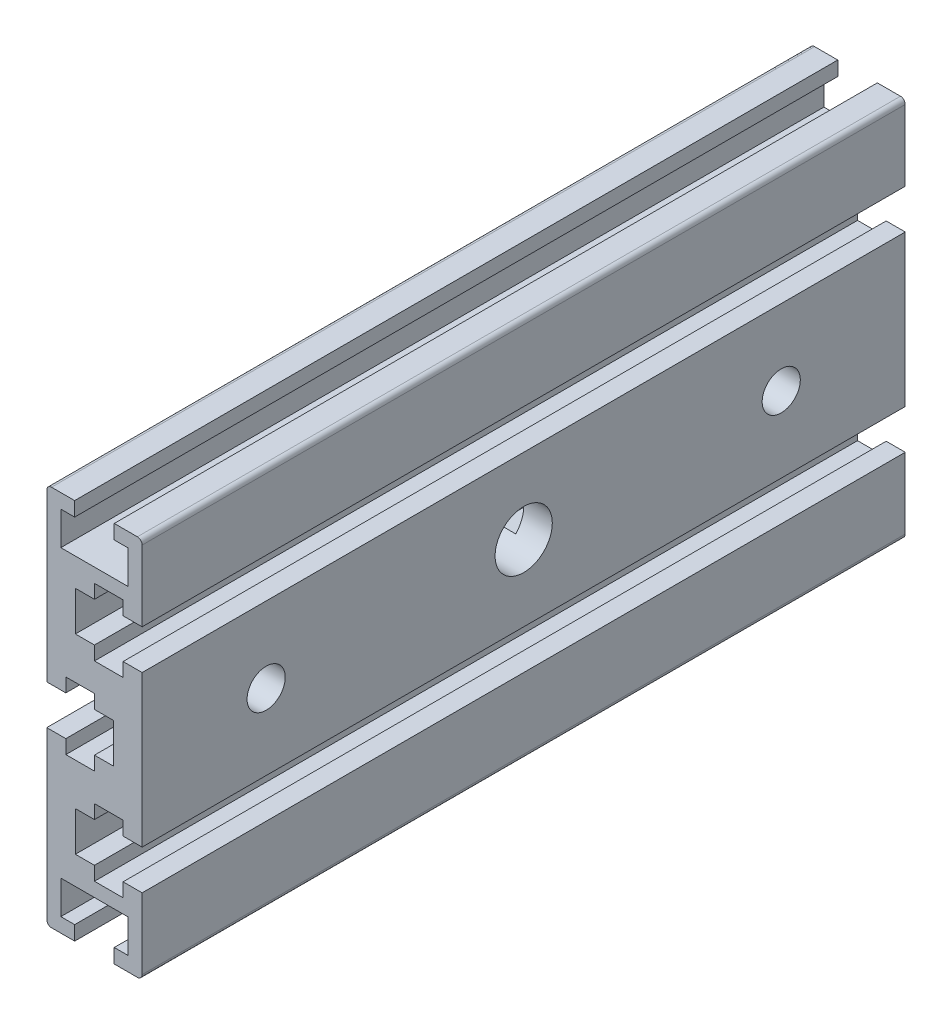
SolidWorks part; units mm, degrees
ref_plane "Plane1" through (0, 0, 0) normal (0, 0, 1) x (1, 0, 0)
ref_plane "Plane2" through (0, 0, 0) normal (0, 1, 0) x (1, 0, 0)
ref_plane "Plane3" through (0, 0, 0) normal (1, 0, 0) x (0, 0, -1)
sketch "Sketch1" plane through (0, 0, 0) normal (0, 0, 1) x (1, 0, 0)
  line L0 (0, 0) -> (75.649, 0) construction
  line L1 (-9, 40) -> (-4.15, 40)
  line L2 (-10, 39) -> (-10, 4.15)
  line L3 (-9, -40) -> (-4.15, -40)
  line L4 (10, 39) -> (10, 24.15)
  line L5 (0, 3.6903) -> (0, 44.6054) construction
  line L6 (-4.15, 40) -> (-4.15, 37)
  line L7 (-4.15, 37) -> (-7.05, 37)
  line L8 (-7.05, 37) -> (-7.05, 30)
  line L9 (-7.05, 30) -> (7.05, 30)
  line L10 (7.05, 30) -> (7.05, 37)
  line L11 (7.05, 37) -> (4.15, 37)
  line L12 (4.15, 37) -> (4.15, 40)
  line L13 (4.15, 40) -> (9, 40)
  line L14 (4.15, -37) -> (4.15, -40)
  line L15 (7.05, -37) -> (4.15, -37)
  line L16 (7.05, -30) -> (7.05, -37)
  line L17 (-7.05, -30) -> (7.05, -30)
  line L18 (-7.05, -37) -> (-7.05, -30)
  line L19 (-4.15, -37) -> (-7.05, -37)
  line L20 (-4.15, -40) -> (-4.15, -37)
  line L21 (4.15, -40) -> (9, -40)
  line L22 (-6, -7.05) -> (0, -7.05)
  line L23 (-10, -4.15) -> (-6, -4.15)
  line L24 (-6, 4.15) -> (-10, 4.15)
  line L25 (0, -7.05) -> (0, -4.15)
  line L26 (-6, -4.15) -> (-6, -7.05)
  line L27 (0, 7.05) -> (-6, 7.05)
  line L28 (-17.4711, 20) -> (26.2798, 20) construction
  line L29 (-6, 7.05) -> (-6, 4.15)
  line L30 (-17.4711, -20) -> (26.2798, -20) construction
  line L31 (-4, -15.85) -> (-4, -24.15)
  line L32 (0, -27.05) -> (0, -24.15)
  line L33 (6, -15.85) -> (10, -15.85)
  line L34 (6, -24.15) -> (6, -27.05)
  line L35 (0, -15.85) -> (0, -12.95)
  line L36 (0, 4.15) -> (4, 4.15)
  line L37 (4, 4.15) -> (4, -4.15)
  line L38 (4, -4.15) -> (0, -4.15)
  line L39 (0, 4.15) -> (0, 7.05)
  line L40 (-10, -4.15) -> (-10, -39)
  line L41 (6, 12.95) -> (6, 15.85)
  line L42 (6, 27.05) -> (0, 27.05)
  line L43 (0, 12.95) -> (6, 12.95)
  line L44 (-4, 24.15) -> (0, 24.15)
  line L45 (10, 24.15) -> (6, 24.15)
  line L46 (0, 15.85) -> (-4, 15.85)
  line L47 (0, 15.85) -> (0, 12.95)
  line L48 (6, 24.15) -> (6, 27.05)
  line L49 (0, -15.85) -> (-4, -15.85)
  line L50 (6, 15.85) -> (10, 15.85)
  line L51 (0, 27.05) -> (0, 24.15)
  line L52 (10, -24.15) -> (6, -24.15)
  line L53 (-4, 15.85) -> (-4, 24.15)
  line L54 (-4, -24.15) -> (0, -24.15)
  line L55 (0, -12.95) -> (6, -12.95)
  line L56 (6, -27.05) -> (0, -27.05)
  line L57 (6, -12.95) -> (6, -15.85)
  line L58 (10, 15.85) -> (10, -15.85)
  line L59 (10, -24.15) -> (10, -39)
  arc A0 (9, -40) -> (10, -39) centre (9, -39) ccw
  arc A1 (-10, -39) -> (-9, -40) centre (-9, -39) ccw
  arc A2 (-9, 40) -> (-10, 39) centre (-9, 39) ccw
  arc A3 (9, 40) -> (10, 39) centre (9, 39) cw
  point P72 (-10, 40)
  point P73 (10, 40)
  point P74 (0, 40)
  point P75 (-10, -40)
  point P76 (10, -40)
  point P77 (0, -40)
  point P78 (10, -20)
  point P79 (-10, 0)
  point P80 (10, 20)
  point P81 (-10, 20)
  point P82 (10, 0)
  point P83 (-10, -20)
extrude "凸台-拉伸1" add sketch "Sketch1" along normal blind 160
hole_wizard "Ø8.0 (8) 直径孔1" positions "草图2" profile "草图1" hole size "Ø8.0" standard "Gb" end condition through all
sketch "草图2" plane through (10, 0, 0) normal (1, 0, 0) x (0, 0, -1)
  line L0 (-160, -15.85) -> (-160, 15.85) construction
  line L2 (-160, -40) -> (0, -40) construction
  point P0 (-134, 0)
  dimension "D1" = 26
  dimension "D2" = 40
sketch "草图1" plane through (10, 0, 134) normal (0, 1, 0) x (0, 0, -1)
  line L0 (0, 0) -> (0, 20)
  line L1 (0, 20) -> (4, 20)
  line L2 (4, 20) -> (4, 0)
  line L5 (4, 0) -> (0, 0)
  line L11 (0, -6.35) -> (0, 107.95) construction
  dimension "通孔孔直径" = 8
  dimension "通孔孔深度" = 20
hole_wizard "Ø8.0 (8) 直径孔2" positions "草图4" profile "草图3" hole size "Ø8.0" standard "Gb"
sketch "草图4" plane through (10, 0, 0) normal (1, 0, 0) x (0, 0, -1)
  line L2 (-160, -40) -> (0, -40) construction
  point P0 (-26, 0)
  dimension "D1" = 134
  dimension "D2" = 40
sketch "草图3" plane through (10, 0, 26) normal (0, 1, 0) x (0, 0, -1)
  line L0 (0, 0) -> (0, 10.4034)
  line L1 (0, 10.4034) -> (4, 8)
  line L2 (4, 8) -> (4, 0)
  line L5 (4, 0) -> (0, 0)
  line L10 (0, 10.4034) -> (-4, 8) construction
  line L11 (0, -6.35) -> (0, 107.95) construction
  dimension "孔直径" = 8
  dimension "孔深度" = 8
  dimension "导头角度" = 118
hole_wizard "Ø12.0 (12) 直径孔2" positions "草图8" profile "草图7" hole size "Ø12.0" standard "Gb" end condition through all
sketch "草图8" plane through (10, 0, 0) normal (1, 0, 0) x (0, 0, -1)
  line L0 (-160, -39) -> (-160, -24.15) construction
  line L2 (-160, -40) -> (0, -40) construction
  point P0 (-80, 0)
  dimension "D1" = 80
  dimension "D2" = 40
sketch "草图7" plane through (10, 0, 80) normal (0, 1, 0) x (0, 0, -1)
  line L0 (0, 0) -> (0, 20)
  line L1 (0, 20) -> (6, 20)
  line L2 (6, 20) -> (6, 0)
  line L5 (6, 0) -> (0, 0)
  line L11 (0, -6.35) -> (0, 107.95) construction
  dimension "通孔孔直径" = 12
  dimension "通孔孔深度" = 20
hole_wizard "Ø5.5 (5.5) 直径孔1" positions "草图10" profile "草图9" hole size "Ø5.5" standard "Gb" end condition through all
sketch "草图10" plane through (-10, 0, 0) normal (-1, 0, 0) x (0, 0, 1)
  line L2 (160, -4.15) -> (160, -39) construction
  line L4 (160, -40) -> (0, -40) construction
  point P0 (103.6, -20)
  dimension "D1" = 20
  dimension "D2" = 56.4
sketch "草图9" plane through (-10, -20, 103.6) normal (0, 1, 0) x (0, 0, 1)
  line L0 (0, 0) -> (0, 20)
  line L1 (0, 20) -> (2.75, 20)
  line L2 (2.75, 20) -> (2.75, 0)
  line L5 (2.75, 0) -> (0, 0)
  line L11 (0, -6.35) -> (0, 107.95) construction
  dimension "通孔孔直径" = 5.5
  dimension "通孔孔深度" = 20
hole_wizard "Ø5.5 (5.5) 直径孔2" positions "草图12" profile "草图11" hole size "Ø5.5" standard "Gb" end condition through all
sketch "草图12" plane through (-10, 0, 0) normal (-1, 0, 0) x (0, 0, 1)
  line L0 (0, -4.15) -> (0, -39) construction
  line L3 (160, -40) -> (0, -40) construction
  point P0 (56.4, -20)
  dimension "D1" = 20
  dimension "D2" = 56.4
sketch "草图11" plane through (-10, -20, 56.4) normal (0, 1, 0) x (0, 0, 1)
  line L0 (0, 0) -> (0, 20)
  line L1 (0, 20) -> (2.75, 20)
  line L2 (2.75, 20) -> (2.75, 0)
  line L5 (2.75, 0) -> (0, 0)
  line L11 (0, -6.35) -> (0, 107.95) construction
  dimension "通孔孔直径" = 5.5
  dimension "通孔孔深度" = 20
hole_wizard "Ø5.5 (5.5) 直径孔3" positions "草图14" profile "草图13" hole size "Ø5.5" standard "Gb" end condition through all
sketch "草图14" plane through (-10, 0, 0) normal (-1, 0, 0) x (0, 0, 1)
  line L3 (160, 39) -> (160, 4.15) construction
  line L4 (160, 40) -> (0, 40) construction
  point P0 (103.6, 20)
  dimension "D1" = 20
  dimension "D3" = 56.4
sketch "草图13" plane through (-10, 20, 103.6) normal (0, 1, 0) x (0, 0, 1)
  line L0 (0, 0) -> (0, 20)
  line L1 (0, 20) -> (2.75, 20)
  line L2 (2.75, 20) -> (2.75, 0)
  line L5 (2.75, 0) -> (0, 0)
  line L11 (0, -6.35) -> (0, 107.95) construction
  dimension "通孔孔直径" = 5.5
  dimension "通孔孔深度" = 20
hole_wizard "Ø5.5 (5.5) 直径孔4" positions "草图16" profile "草图15" hole size "Ø5.5" standard "Gb" end condition through all
sketch "草图16" plane through (-10, 0, 0) normal (-1, 0, 0) x (0, 0, 1)
  line L1 (0, 39) -> (0, 4.15) construction
  line L3 (160, 40) -> (0, 40) construction
  point P0 (56.4, 20)
  dimension "D1" = 56.4
  dimension "D2" = 20
sketch "草图15" plane through (-10, 20, 56.4) normal (0, 1, 0) x (0, 0, 1)
  line L0 (0, 0) -> (0, 20)
  line L1 (0, 20) -> (2.75, 20)
  line L2 (2.75, 20) -> (2.75, 0)
  line L5 (2.75, 0) -> (0, 0)
  line L11 (0, -6.35) -> (0, 107.95) construction
  dimension "通孔孔直径" = 5.5
  dimension "通孔孔深度" = 20
hole_wizard "M5 螺纹孔1" positions "草图18" profile "草图17" tap size "M5" standard "Gb" end condition through all
sketch "草图18" plane through (-10, 0, 0) normal (-1, 0, 0) x (0, 0, 1)
  line L1 (0, -4.15) -> (0, -39) construction
  line L2 (160, -40) -> (0, -40) construction
  point P0 (80, -18.25)
  dimension "D1" = 21.75
  dimension "D2" = 80
sketch "草图17" plane through (-10, -18.25, 80) normal (0, 1, 0) x (0, 0, 1)
  line L0 (0, 0) -> (0, 20)
  line L1 (0, 20) -> (2.1, 20)
  line L2 (2.1, 20) -> (2.1, 0)
  line L5 (2.1, 0) -> (0, 0)
  line L11 (0, -6.35) -> (0, 107.95) construction
  dimension "通孔螺纹孔钻头直径" = 4.2
  dimension "通孔螺纹孔钻头深度" = 20
cosmetic thread "孔螺蚊线1" parameters "D2"=5
hole_wizard "M5 螺纹孔2" positions "草图20" profile "草图19" tap size "M5" standard "Gb" end condition through all
sketch "草图20" plane through (-10, 0, 0) normal (-1, 0, 0) x (0, 0, 1)
  line L1 (160, 39) -> (160, 4.15) construction
  line L2 (160, 40) -> (0, 40) construction
  point P0 (80, 18.25)
  dimension "D1" = 21.75
  dimension "D2" = 80
sketch "草图19" plane through (-10, 18.25, 80) normal (0, 1, 0) x (0, 0, 1)
  line L0 (0, 0) -> (0, 20)
  line L1 (0, 20) -> (2.1, 20)
  line L2 (2.1, 20) -> (2.1, 0)
  line L5 (2.1, 0) -> (0, 0)
  line L11 (0, -6.35) -> (0, 107.95) construction
  dimension "通孔螺纹孔钻头直径" = 4.2
  dimension "通孔螺纹孔钻头深度" = 20
cosmetic thread "孔螺蚊线2" parameters "D2"=5
